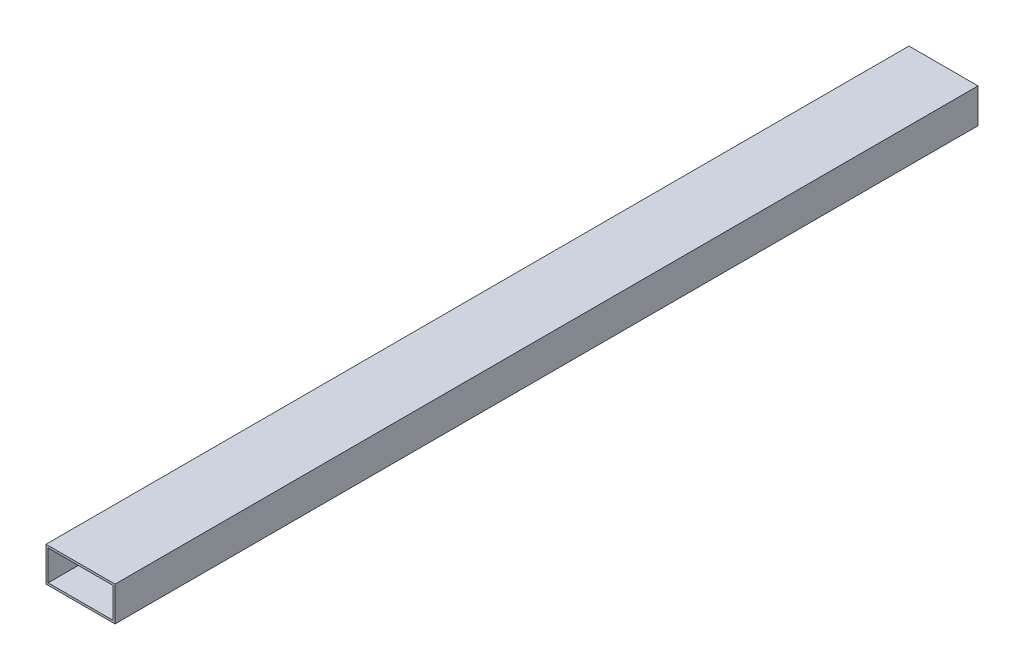
SolidWorks part; units mm, degrees
ref_plane "Front Plane" through (0, 0, 0) normal (0, 0, 1) x (1, 0, 0)
ref_plane "Top Plane" through (0, 0, 0) normal (0, 1, 0) x (1, 0, 0)
ref_plane "Right Plane" through (0, 0, 0) normal (1, 0, 0) x (0, 0, -1)
sketch "Sketch1" plane through (0, 0, 0) normal (0, 0, 1) x (1, 0, 0)
  line L0 (-23.8125, 11.1125) -> (23.8125, 11.1125)
  line L2 (-25.4, 12.7) -> (25.4, 12.7)
  line L3 (-25.4, 12.7) -> (-25.4, -12.7)
  line L4 (-25.4, -12.7) -> (25.4, -12.7)
  line L5 (25.4, 12.7) -> (25.4, -12.7)
  line L10 (23.8125, 11.1125) -> (23.8125, -11.1125)
  line L11 (-23.8125, -11.1125) -> (23.8125, -11.1125)
  line L12 (-23.8125, 11.1125) -> (-23.8125, -11.1125)
  point P12 (0, 12.7)
  point P14 (25.4, 0)
  dimension "Wall Thickness" = 1.5875
  dimension "Outside Width" = 50.8
  dimension "Outside Height" = 25.4
  dimension "Inside Height" = 22.225
  dimension "Inside Width" = 47.625
sketch "Sketch2" plane through (0, 0, 0) normal (1, 0, 0) x (0, 0, -1)
  line L0 (317.5, 0) -> (-317.5, 0)
  point P4 (0, 0)
  point P7 (-317.5, 0)
  point P10 (317.5, 0)
  dimension "Length" = 635
sketch "Sketch3" plane through (0, 0, 0) normal (0, 0, 1) x (1, 0, 0)
  line L21 (25.4, 12.7) -> (-25.4, 12.7)
  line L22 (25.4, -12.7) -> (25.4, 12.7)
  line L23 (-25.4, -12.7) -> (25.4, -12.7)
  line L24 (-25.4, 12.7) -> (-25.4, -12.7)
  line L25 (25.4, 12.7) -> (-25.4, 12.7)
  line L26 (25.4, -12.7) -> (25.4, 12.7)
  line L27 (-25.4, -12.7) -> (25.4, -12.7)
  line L28 (-25.4, 12.7) -> (-25.4, -12.7)
  line L29 (23.8125, 11.1125) -> (-23.8125, 11.1125)
  line L30 (23.8125, -11.1125) -> (23.8125, 11.1125)
  line L31 (-23.8125, -11.1125) -> (23.8125, -11.1125)
  line L32 (-23.8125, 11.1125) -> (-23.8125, -11.1125)
  line L33 (23.8125, 11.1125) -> (-23.8125, 11.1125)
  line L34 (23.8125, -11.1125) -> (23.8125, 11.1125)
  line L35 (-23.8125, -11.1125) -> (23.8125, -11.1125)
  line L36 (-23.8125, 11.1125) -> (-23.8125, -11.1125)
  dimension "D1" = 0
  dimension "D2" = 0
extrude "Boss-Extrude1" add sketch "Sketch3" along normal up to vertex (317.5 mm away) and the other way up to vertex (317.5 mm away) up to point (0, 0, 317.5) other way up to point (0, 0, -317.5)
sketch "Drawing Reference" plane through (0, 0, 0) normal (1, 0, 0) x (0, 0, -1)
  line L0 (-317.5, 0) -> (317.5, 0) construction
  line L1 (0, -12.7) -> (0, 12.7) construction
  line L2 (-317.5, -12.7) -> (317.5, -12.7) construction
  line L5 (-317.5, 12.7) -> (317.5, 12.7) construction
  point P7 (-280.924, 0)
  point P8 (280.924, 0)
  dimension "D1" = 36.576
equation "\"D1@Drawing Reference\"=\"Outside Width@Sketch1\" * 0.72"
